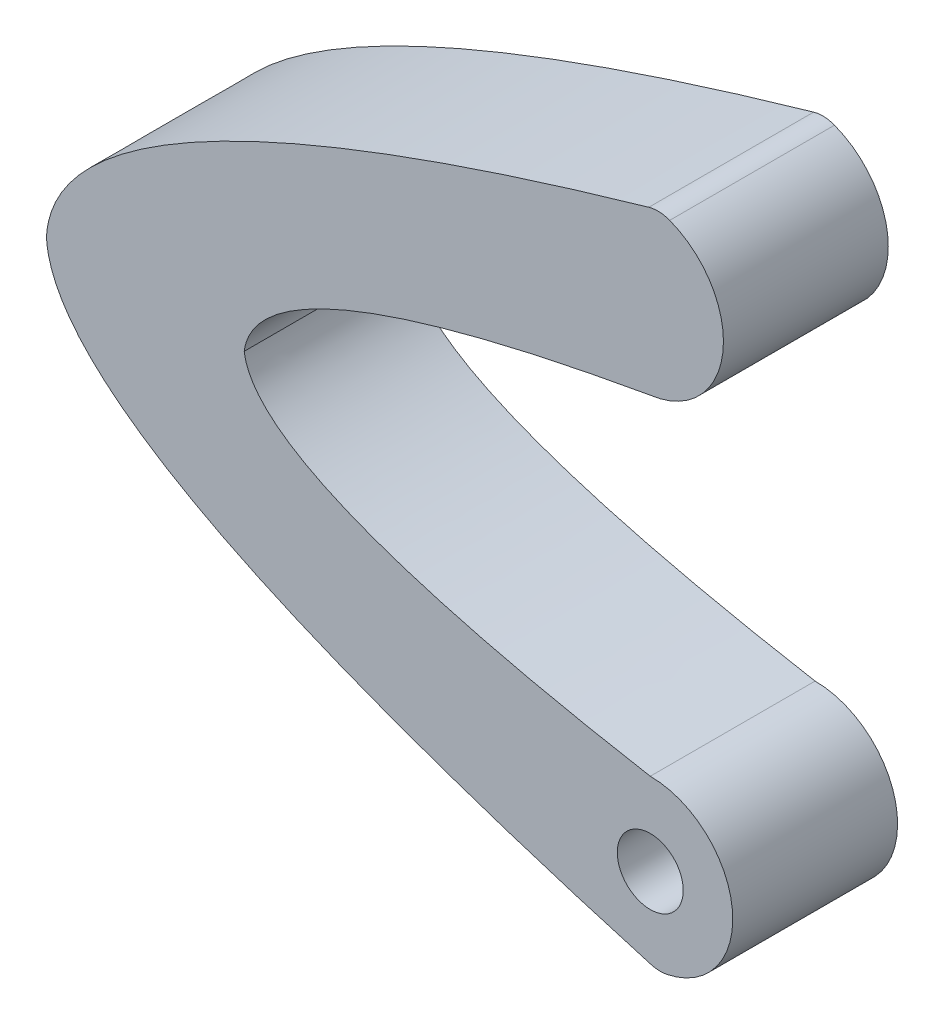
SolidWorks part; units mm, degrees
ref_plane "Front Plane" through (0, 0, 0) normal (0, 0, 1) x (1, 0, 0)
ref_plane "Top Plane" through (0, 0, 0) normal (0, 1, 0) x (1, 0, 0)
ref_plane "Right Plane" through (0, 0, 0) normal (1, 0, 0) x (0, 0, -1)
sketch "Sketch1" plane through (0, 0, 0) normal (0, 0, 1) x (1, 0, 0)
  arc A2 (47.5152, 28.6367) -> (47.0466, 18.6477) centre (46.4117, 23.683) cw
  arc A5 (47.5152, -11.3633) -> (47.0466, -1.3743) centre (47.0466, -6.3798) ccw
  circle A6 centre (47.0466, -6.3798) radius 2
  spline S0 degree 2 poles (47.5152, 28.6367) (10.9333, 18.1994) (10.4117, 8.6362) knots 0 0 0 0.478869 0.478869 0.478869
  spline S1 degree 2 poles (47.0466, 18.6477) (23.1495, 14.4157) (22.4117, 8.6362) knots 0 0 0 0.485397 0.485397 0.485397
  spline S2 degree 2 poles (47.0466, -1.3743) (23.1495, 2.8567) (22.4117, 8.6362) knots 0 0 0 0.485397 0.485397 0.485397
  spline S3 degree 2 poles (47.5152, -11.3633) (10.9333, -0.927) (10.4117, 8.6362) knots 0 0 0 0.478869 0.478869 0.478869
  point P0 (0, 0)
  point P22 (22.7464, 0)
  dimension "D5" = 36
  dimension "D1" = 4
  dimension "D2" = 40
  dimension "D3" = 12
  dimension "D4" = 10
extrude "Boss-Extrude2" add sketch "Sketch1" along normal blind 10
fillet "Fillet4" radius 2 1 edges at (47.5152, 28.6367, 5)
fillet "Fillet5" radius 2 1 edges at (47.5152, -11.3633, 5)
